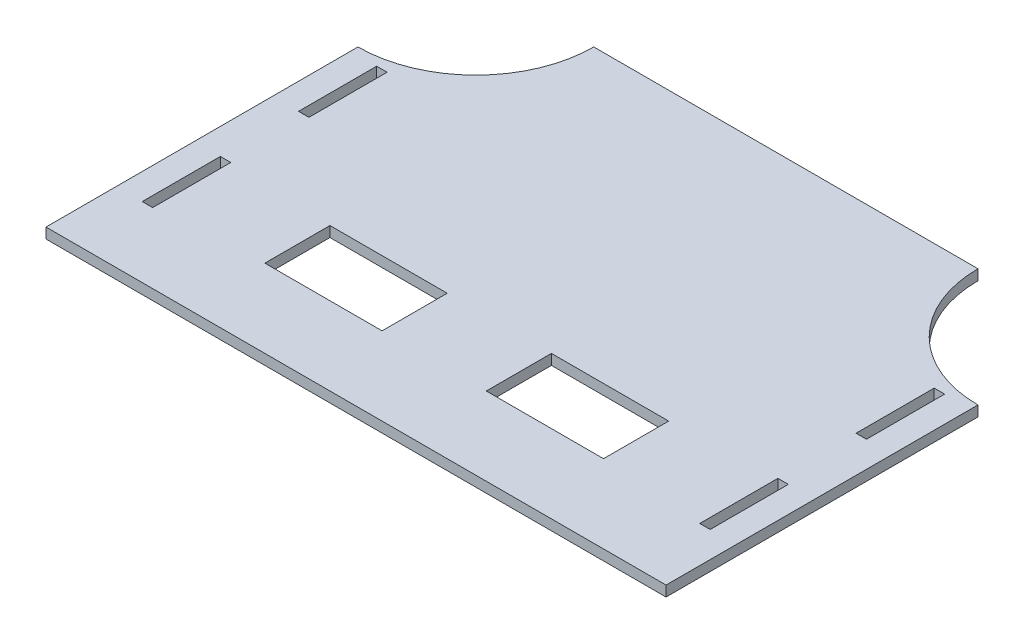
SolidWorks part; units mm, degrees
ref_plane "Front Plane" through (0, 0, 0) normal (0, 0, 1) x (1, 0, 0)
ref_plane "Top Plane" through (0, 0, 0) normal (0, 1, 0) x (1, 0, 0)
ref_plane "Right Plane" through (0, 0, 0) normal (1, 0, 0) x (0, 0, -1)
sketch "Sketch2" plane through (0, 0, 0) normal (0, 1, 0) x (1, 0, 0)
  line L1 (0, 0) -> (238, 0)
  line L2 (0, 0) -> (0, 165)
  line L3 (0, 165) -> (238, 165)
  line L4 (238, 0) -> (238, 165)
  dimension "D1" = 238
  dimension "D2" = 165
extrude "Boss-Extrude1" add sketch "Sketch2" along normal blind 4
sketch "Sketch3" plane through (0, 4, 0) normal (0, 1, 0) x (1, 0, 0)
  line L1 (228, 116.9319) -> (224, 116.9319)
  line L2 (228, 116.9319) -> (228, 86.9319)
  line L3 (228, 86.9319) -> (224, 86.9319)
  line L4 (224, 116.9319) -> (224, 86.9319)
  line L5 (228, 56.9319) -> (224, 56.9319)
  line L6 (228, 56.9319) -> (228, 26.9319)
  line L7 (228, 26.9319) -> (224, 26.9319)
  line L8 (224, 56.9319) -> (224, 26.9319)
  line L9 (14, 116.9319) -> (10, 116.9319)
  line L10 (14, 116.9319) -> (14, 86.9319)
  line L11 (14, 86.9319) -> (10, 86.9319)
  line L12 (10, 116.9319) -> (10, 86.9319)
  line L13 (14, 56.9319) -> (10, 56.9319)
  line L14 (14, 56.9319) -> (14, 26.9319)
  line L15 (14, 26.9319) -> (10, 26.9319)
  line L16 (10, 56.9319) -> (10, 26.9319)
extrude "Cut-Extrude1" cut sketch "Sketch3" against normal through all
sketch "Sketch5" plane through (0, 4, 0) normal (0, 1, 0) x (1, 0, 0)
  circle A0 centre (238, 165) radius 45.2615
  circle A1 centre (0, 165) radius 45.2615
extrude "Cut-Extrude3" cut sketch "Sketch5" against normal blind 10
sketch "Sketch7" plane through (0, 4, 0) normal (0, 1, 0) x (1, 0, 0)
  line L0 (119, 0) -> (119, 162.7068) construction
  line L2 (0, 0) -> (238, 0) construction
sketch "Sketch8" plane through (0, 4, 0) normal (0, 1, 0) x (1, 0, 0)
  line L5 (54, 55) -> (99, 55)
  line L6 (54, 55) -> (54, 30)
  line L7 (54, 30) -> (99, 30)
  line L8 (99, 55) -> (99, 30)
  line L9 (0, 0) -> (238, 0) construction
  line L11 (139, 55) -> (184, 55)
  line L12 (139, 55) -> (139, 30)
  line L14 (139, 30) -> (184, 30)
  line L15 (184, 55) -> (184, 30)
  line L17 (119, 0) -> (119, 162.7068) construction
  point P4 (139, 42.5)
  dimension "D1" = 45
  dimension "D2" = 25
  dimension "D3" = 40
  dimension "D4" = 45
  dimension "D5" = 25
  dimension "D6" = 30
  dimension "D7" = 30
  dimension "D8" = 20
extrude "Cut-Extrude4" cut sketch "Sketch8" against normal through all
